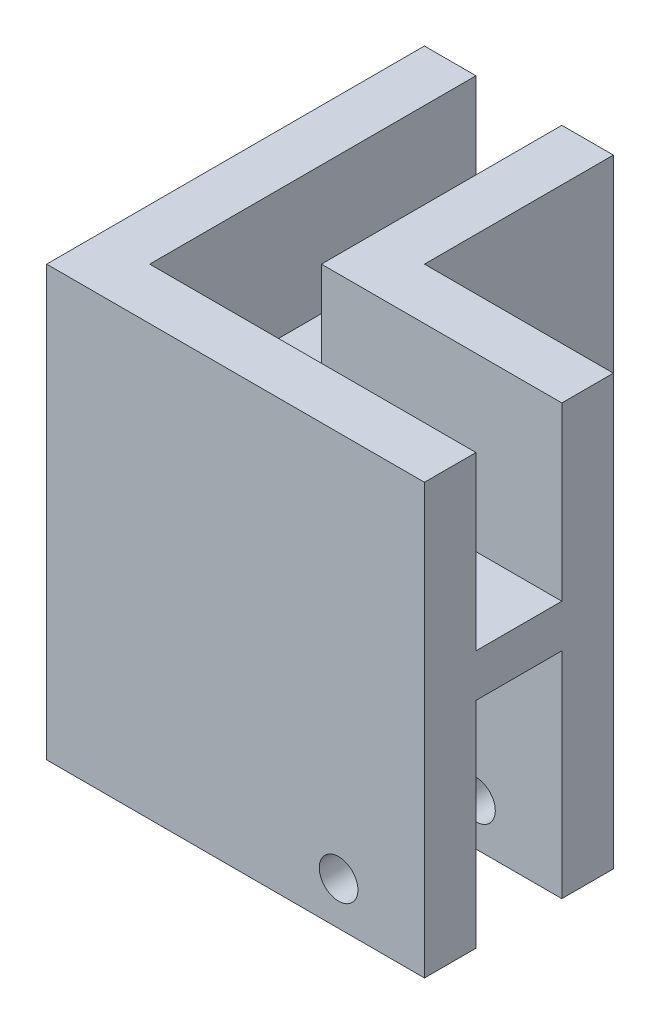
SolidWorks part; units mm, degrees
material "ABS"
ref_plane "Piano frontale" through (0, 0, 0) normal (0, 0, 1) x (1, 0, 0)
ref_plane "Piano superiore" through (0, 0, 0) normal (0, 1, 0) x (1, 0, 0)
ref_plane "Piano destro" through (0, 0, 0) normal (1, 0, 0) x (0, 0, -1)
sketch "Schizzo2" plane through (0, 0, 0) normal (0, 0, 1) x (1, 0, 0)
  line L0 (0, 0) -> (-10, 0)
  line L1 (-10, 0) -> (-10, -25)
  line L2 (-10, -25) -> (-16, -25)
  line L3 (-16, -25) -> (-16, 25)
  line L4 (-16, 25) -> (-10, 25)
  line L5 (-10, 25) -> (-10, 10)
  line L6 (-10, 10) -> (0, 10)
  line L7 (0, 10) -> (0, 25)
  line L8 (0, 25) -> (6, 25)
  line L9 (6, 25) -> (6, -25)
  line L10 (6, -25) -> (0, -25)
  line L11 (0, -25) -> (0, 0)
  dimension "D1" = 10
  dimension "D2" = 50
  dimension "D3" = 6
  dimension "D4" = 10
  dimension "D5" = 25
extrude "Estrusione-Estrusione1" add sketch "Schizzo2" along normal blind 28
sketch "Schizzo3" plane through (6, 0, 0) normal (1, 0, 0) x (0, 0, -1)
  line L3 (-28, 0) -> (-38, 0)
  line L4 (-38, 0) -> (-38, -25)
  line L5 (-38, -25) -> (-44, -25)
  line L6 (-44, -25) -> (-44, 25)
  line L7 (-44, 25) -> (-38, 25)
  line L8 (-38, 25) -> (-38, 10)
  line L9 (-38, 10) -> (-28, 10)
  line L12 (-28, -25) -> (-28, 25) construction
  line L13 (-38, 25) -> (-28, 25) construction
  line L14 (-28, 10) -> (-28, 0)
  dimension "D1" = 10
  dimension "D2" = 6
  dimension "D3" = 50
  dimension "D4" = 10
  dimension "D5" = 25
extrude "Estrusione-Estrusione2" add sketch "Schizzo3" against normal blind 16
sketch "Schizzo4" plane through (-10, 0, 0) normal (-1, 0, 0) x (0, 0, 1)
  line L0 (28, 25) -> (44, 25)
  line L1 (44, 25) -> (44, -25)
  line L2 (44, -25) -> (28, -25)
  line L3 (28, -25) -> (28, 25)
extrude "Estrusione-Estrusione3" add sketch "Schizzo4" along normal blind 6
sketch "Schizzo5" plane through (6, 0, 0) normal (1, 0, 0) x (0, 0, -1)
  line L0 (-38, -25) -> (-44, -25)
  line L1 (-44, -25) -> (-44, 25)
  line L2 (-44, 25) -> (-38, 25)
  line L3 (-38, 25) -> (-38, 5)
  line L4 (-38, 5) -> (-28, 5)
  line L7 (-28, 5) -> (-28, 25)
  line L8 (-28, 25) -> (-22, 25)
  line L9 (-28, 25) -> (0, 25) construction
  line L10 (-22, 25) -> (-22, -25)
  line L11 (-28, -25) -> (0, -25) construction
  line L12 (-22, -25) -> (-28, -25)
  line L13 (-28, -25) -> (-28, 0)
  line L14 (-28, 0) -> (-38, 0)
  line L15 (-38, 0) -> (-38, -25)
  dimension "D1" = 5
extrude "Estrusione-Estrusione4" add sketch "Schizzo5" along normal blind 22
hole_wizard "Foro per Vite M4-1" positions "Schizzo6" profile "Schizzo7" hole size "M4" standard "ISO"
sketch "Schizzo6" plane through (0, 0, 44) normal (0, 0, 1) x (1, 0, 0)
  line L0 (-16, -25) -> (-16, 25) construction
  point P0 (18, -20)
  dimension "D1" = 34
  dimension "D2" = 20
sketch "Schizzo7" plane through (18, -20, 44) normal (1, 0, 0) x (0, -1, 0)
  line L0 (0, 0) -> (0, 31.3519)
  line L1 (0, 31.3519) -> (2.25, 30)
  line L2 (2.25, 30) -> (2.25, 0)
  line L5 (2.25, 0) -> (0, 0)
  line L10 (0, 31.3519) -> (-2.25, 30) construction
  line L11 (0, -6.35) -> (0, 107.95) construction
  dimension "Hole Dia." = 4.5
  dimension "Hole Depth" = 30
  dimension "Drill Angle" = 118
hole_wizard "Foro per Vite M4-2" positions "Schizzo8" profile "Schizzo9" hole size "M4" standard "ISO"
sketch "Schizzo8" plane through (-16, 0, 0) normal (-1, 0, 0) x (0, 0, 1)
  line L0 (44, -25) -> (44, 25) construction
  point P0 (10, -20)
  dimension "D1" = 34
  dimension "D2" = 20
sketch "Schizzo9" plane through (-16, -20, 10) normal (0, 1, 0) x (0, 0, 1)
  line L0 (0, 0) -> (0, 31.3519)
  line L1 (0, 31.3519) -> (2.25, 30)
  line L2 (2.25, 30) -> (2.25, 0)
  line L5 (2.25, 0) -> (0, 0)
  line L10 (0, 31.3519) -> (-2.25, 30) construction
  line L11 (0, -6.35) -> (0, 107.95) construction
  dimension "Hole Dia." = 4.5
  dimension "Hole Depth" = 30
  dimension "Drill Angle" = 118
sketch "Schizzo10" plane through (6, 0, 0) normal (1, 0, 0) x (0, 0, -1)
  line L1 (-38, 10) -> (-28, 10)
  line L2 (-38, 10) -> (-38, 5)
  line L3 (-38, 5) -> (-28, 5)
  line L4 (-28, 10) -> (-28, 5)
extrude "Taglio-Estrusione1" cut sketch "Schizzo10" against normal blind 6
